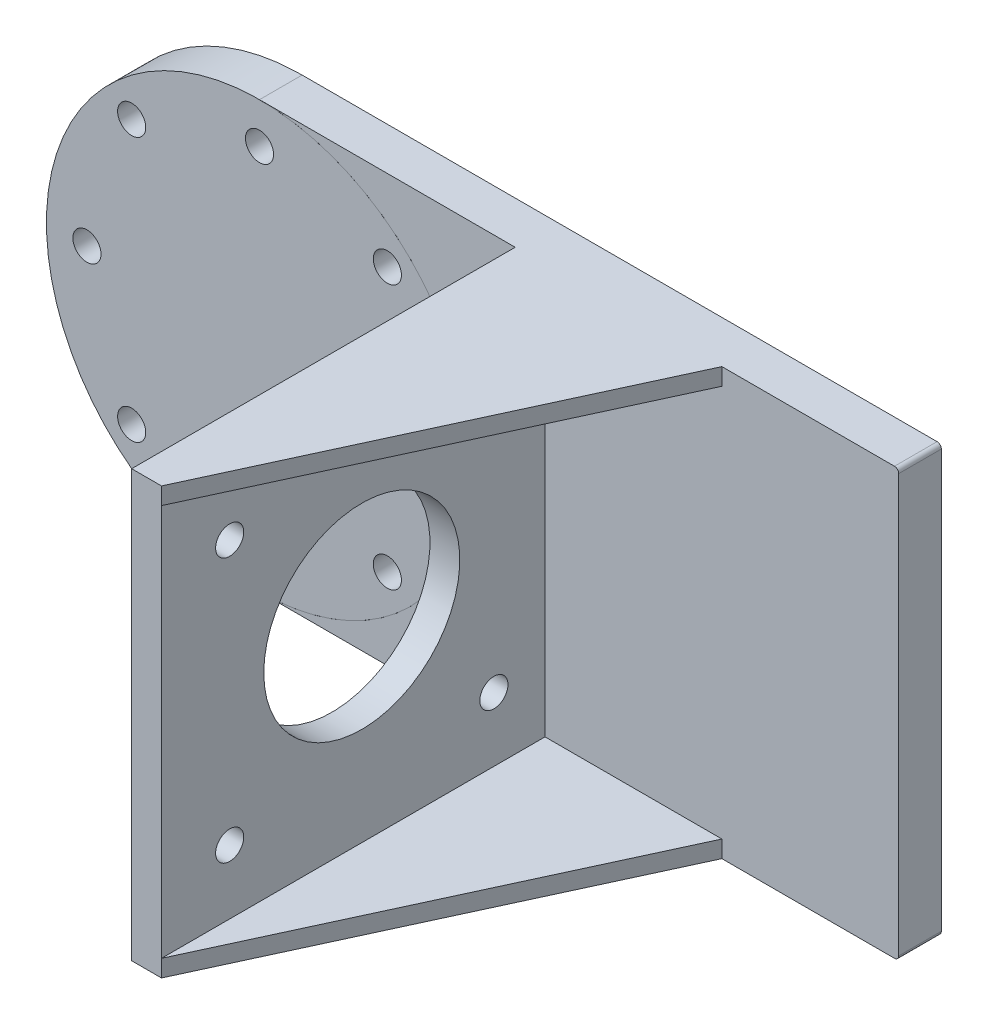
SolidWorks part; units mm, degrees
ref_plane "前视基准面" through (0, 0, 0) normal (0, 0, 1) x (1, 0, 0)
ref_plane "上视基准面" through (0, 0, 0) normal (0, 1, 0) x (1, 0, 0)
ref_plane "右视基准面" through (0, 0, 0) normal (1, 0, 0) x (0, 0, -1)
sketch "草图1" plane through (0, 0, 0) normal (0, 0, 1) x (1, 0, 0)
  circle A0 centre (0, 0) radius 25
  dimension "D1" = 50
extrude "凸台-拉伸1" add sketch "草图1" along normal blind 5
sketch "草图3" plane through (0, 0, 5) normal (0, 0, 1) x (1, 0, 0)
  line L0 (0, 0) -> (25, 0) construction
  line L1 (0, 0) -> (0, -25) construction
  line L2 (0, 0) -> (0, 20.25) construction
  line L3 (0, 0) -> (-20.25, 0) construction
  line L4 (0, 0) -> (0, 15.5) construction
  line L5 (0, 15.5) -> (15, 15.5) construction
  circle A0 centre (0, 0) radius 25 construction
  circle A1 centre (0, 20.25) radius 1.65
  circle A2 centre (-20.25, 0) radius 1.65
  circle A3 centre (0, -20.25) radius 1.65
  circle A4 centre (20.25, 0) radius 1.65
  circle A5 centre (15, 15.5) radius 1.65
  circle A6 centre (15, -15.5) radius 1.65
  circle A7 centre (-15, -15.5) radius 1.65
  circle A8 centre (-15, 15.5) radius 1.65
  dimension "D3" = 3.3
  dimension "D4" = 3.3
  dimension "D7" = 3.3
  dimension "D1" = 20.25
  dimension "D2" = 20.25
  dimension "D5" = 15.5
  dimension "D6" = 15
extrude "切除-拉伸1" cut sketch "草图3" against normal blind 5
sketch "草图4" plane through (0, 0, 5) normal (0, 0, 1) x (1, 0, 0)
  line L0 (0, 0) -> (22, 0) construction
  line L1 (0, 25) -> (30, 25)
  line L2 (0, -25) -> (30, -25)
  line L3 (30, 25) -> (30, -25)
  line L4 (30, 25) -> (75, 25)
  line L5 (30, -25) -> (75, -25)
  line L6 (75, 25) -> (75, -25)
  circle A0 centre (0, 0) radius 25 construction
  arc A1 (0, -25) -> (0, 25) centre (0, 0) ccw
  circle M16 centre (0, 0) radius 25
  dimension "D2" = 30
  dimension "D4" = 50
  dimension "D1" = 22
  dimension "D3" = 30
  dimension "D5" = 45
  dimension "D6" = 45
extrude "凸台-拉伸2" add sketch "草图4" against normal blind 5 separate body contours L3 L1 L2 M16 | L6 L4 L3 L5
sketch "草图6" plane through (0, 0, 5) normal (0, 0, 1) x (1, 0, 0)
  line L0 (0, 25) -> (30, 25) construction
  line L1 (0, 25) -> (75, 25) construction
  line L2 (30, 25) -> (30, -25)
  line L3 (0, -25) -> (75, -25) construction
  line L4 (30, -25) -> (33.5, -25)
  line L5 (33.5, -25) -> (33.5, 25)
  line L6 (33.5, 25) -> (30, 25)
extrude "凸台-拉伸3" add sketch "草图6" along normal blind 45
sketch "草图7" plane through (30, 0, 0) normal (-1, 0, 0) x (0, 0, 1)
  line L0 (5, 25) -> (48, 25) construction
  line L1 (50, 25) -> (5, 25) construction
  line L2 (5, -25) -> (26.5, -25) construction
  line L3 (50, -25) -> (5, -25) construction
  line L4 (26.5, -25) -> (26.5, 25) construction
  line L5 (50, 0) -> (26.5, 0) construction
  line L6 (50, 25) -> (50, -25) construction
  line L7 (26.5, 0) -> (42, 0) construction
  line L8 (42, 0) -> (42, 15.5) construction
  circle A0 centre (26.5, 0) radius 11.5
  circle A1 centre (42, 15.5) radius 1.65
  circle A2 centre (42, -15.5) radius 1.65
  circle A3 centre (11, -15.5) radius 1.65
  circle A4 centre (11, 15.5) radius 1.65
  dimension "D2" = 23
  dimension "D3" = 3.3
  dimension "D1" = 21.5
extrude "切除-拉伸2" cut sketch "草图7" against normal blind 45
sketch "草图9" plane through (0, -25, 0) normal (0, -1, 0) x (1, 0, 0)
  line L0 (33.5, 5) -> (54.25, 5)
  line L1 (33.5, 5) -> (75, 5) construction
  line L2 (54.25, 5) -> (33.5, 50)
  line L3 (33.5, 50) -> (33.5, 5)
extrude "凸台-拉伸4" add sketch "草图9" against normal blind 2
sketch "草图10" plane through (0, 25, 0) normal (0, 1, 0) x (1, 0, 0)
  line L0 (33.5, -50) -> (54.25, -5)
  line L1 (33.5, -5) -> (75, -5) construction
  line L2 (54.25, -5) -> (33.5, -5)
  line L3 (33.5, -5) -> (33.5, -50)
extrude "凸台-拉伸5" add sketch "草图10" against normal blind 2
fillet "圆角1" radius 0.5 2 edges at (75, 25, 2.5) (75, -25, 2.5)
